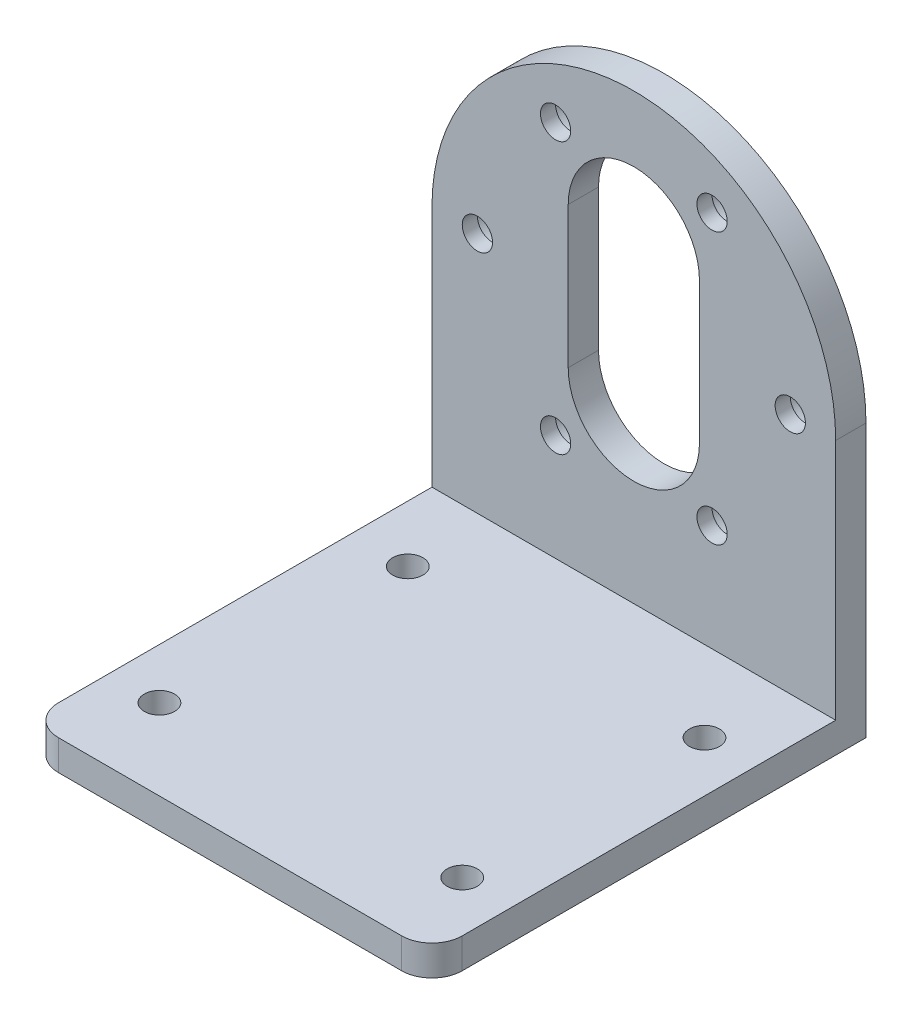
SolidWorks part; units mm, degrees
ref_plane "前视基准面" through (0, 0, 0) normal (0, 0, 1) x (1, 0, 0)
ref_plane "上视基准面" through (0, 0, 0) normal (0, 1, 0) x (1, 0, 0)
ref_plane "右视基准面" through (0, 0, 0) normal (1, 0, 0) x (0, 0, -1)
sketch "草图1" plane through (0, 0, 0) normal (0, 0, 1) x (1, 0, 0)
  line L0 (-20, 0) -> (20, 0)
  line L1 (0, 0) -> (0, 45.8608) construction
  line L2 (-20, 27) -> (-20, 0)
  line L3 (20, 27) -> (20, 0)
  arc A0 (20, 27) -> (-20, 27) centre (0, 27) ccw
  dimension "D4" = 40
  dimension "D1" = 40
  dimension "D2" = 20
  dimension "D3" = 27
extrude "凸台-拉伸1" add sketch "草图1" along normal blind 3
sketch "草图2" plane through (0, 0, 3) normal (0, 0, 1) x (1, 0, 0)
  line L0 (20, 0) -> (20, 27) construction
  line L1 (-20, 0) -> (20, 0)
  line L2 (-20, 0) -> (-20, 3)
  line L3 (-20, 3) -> (20, 3)
  line L4 (20, 0) -> (20, 3)
  dimension "D1" = 3
extrude "凸台-拉伸2" add sketch "草图2" along normal blind 40
sketch "草图3" plane through (0, 0, 0) normal (0, 0, -1) x (-1, 0, 0)
  line L0 (-22.6423, 27) -> (22.1829, 27) construction
  circle A0 centre (-15.5, 27) radius 2.5
  arc A1 (20, 27) -> (-20, 27) centre (0, 27) ccw construction
  circle A2 centre (-7.75, 40.4234) radius 2.5
  circle A3 centre (7.75, 40.4234) radius 2.5
  circle A4 centre (15.5, 27) radius 2.5
  circle A5 centre (7.75, 13.5766) radius 2.5
  circle A6 centre (-7.75, 13.5766) radius 2.5
  point P20 (0, 27)
  dimension "D1" = 5
  dimension "D2" = 15.5
  dimension "D3" = 6
extrude "切除-拉伸1" cut sketch "草图3" against normal blind 1.5
sketch "草图4" plane through (0, 0, 1.5) normal (0, 0, -1) x (-1, 0, 0)
  circle A0 centre (-15.5, 27) radius 1.5
  circle A1 centre (-7.75, 40.4234) radius 1.5
  circle A2 centre (7.75, 40.4234) radius 1.5
  circle A3 centre (15.5, 27) radius 1.5
  circle A4 centre (7.75, 13.5766) radius 1.5
  circle A5 centre (-7.75, 13.5766) radius 1.5
  point P15 (0, 27)
  dimension "D1" = 3
  dimension "D2" = 6
extrude "切除-拉伸2" cut sketch "草图4" against normal through all
sketch "草图5" plane through (0, 0, 0) normal (0, -1, 0) x (1, 0, 0)
  line L0 (-20, 43) -> (20, 43) construction
  line L1 (20, 43) -> (20, 0) construction
  circle A0 centre (-15, 35) radius 1.5
  circle A1 centre (15, 35) radius 1.5
  circle A2 centre (-14.3941, 11) radius 1.5
  circle A3 centre (15, 11) radius 1.5
  dimension "D1" = 3
  dimension "D2" = 3
  dimension "D3" = 3
  dimension "D4" = 3
  dimension "D6" = 8
  dimension "D7" = 24
  dimension "D8" = 8
  dimension "D9" = 30
  dimension "D10" = 5
  dimension "D5" = 24
extrude "切除-拉伸3" cut sketch "草图5" against normal through all
fillet "圆角1" radius 3 2 edges at (20, 1.5, 43) (-20, 1.5, 43)
sketch "草图6" plane through (0, 0, 0) normal (0, 0, -1) x (-1, 0, 0)
  line L0 (0, 47) -> (0, 0) construction
  line L1 (-20, 27) -> (20, 27) construction
  line L2 (-6.5, 34) -> (-6.5, 20)
  line L3 (6.5, 34) -> (6.5, 20)
  arc A0 (20, 27) -> (-20, 27) centre (0, 27) ccw construction
  arc A1 (6.5, 34) -> (-6.5, 34) centre (0, 34) ccw
  arc A2 (-6.5, 20) -> (6.5, 20) centre (0, 20) ccw
  dimension "D1" = 13
  dimension "D2" = 13
  dimension "D3" = 7
  dimension "D4" = 7
extrude "切除-拉伸4" cut sketch "草图6" against normal up to next
